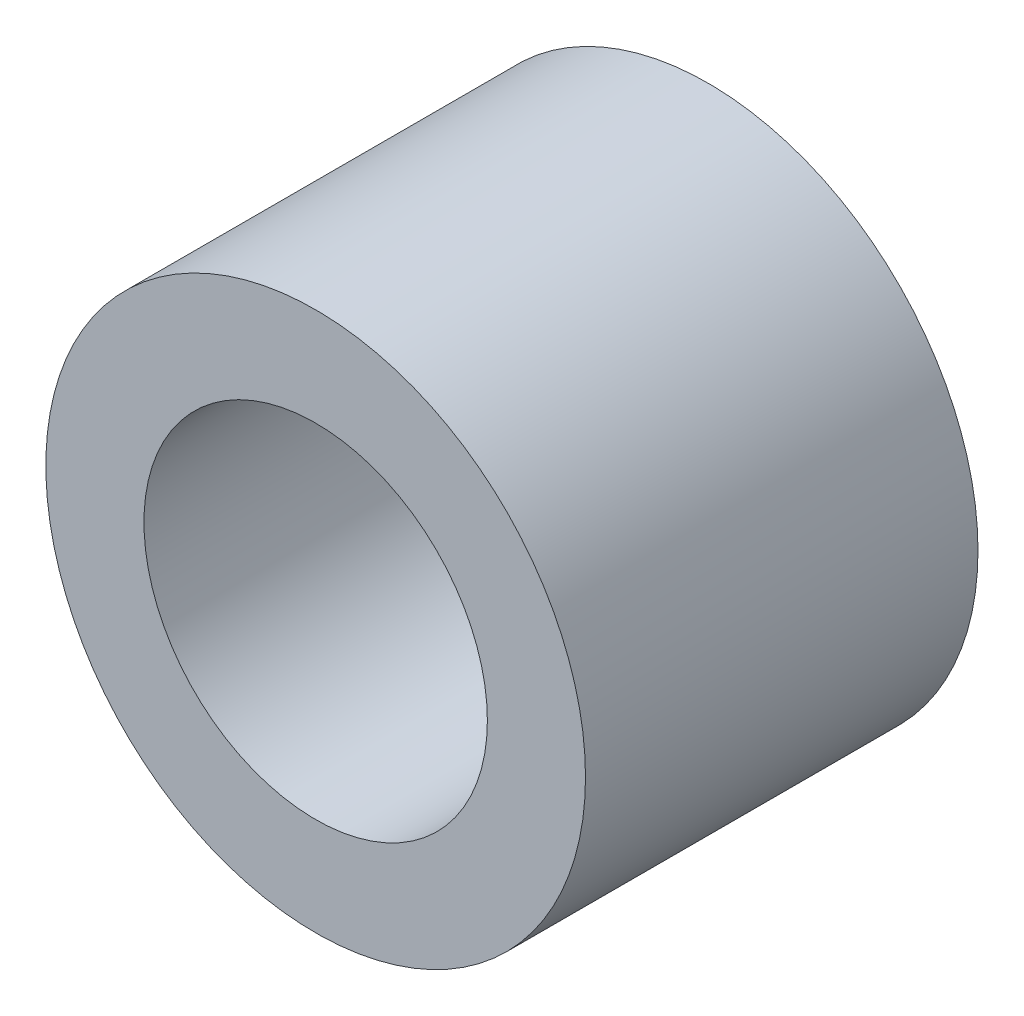
SolidWorks part; units mm, degrees
material "ABS"
ref_plane "前视基准面" through (0, 0, 0) normal (0, 0, 1) x (1, 0, 0)
ref_plane "上视基准面" through (0, 0, 0) normal (0, 1, 0) x (1, 0, 0)
ref_plane "右视基准面" through (0, 0, 0) normal (1, 0, 0) x (0, 0, -1)
sketch "草图1" plane through (0, 0, 0) normal (0, 0, 1) x (1, 0, 0)
  circle A0 centre (0, 0) radius 1.75
  circle A1 centre (0, 0) radius 2.75
  dimension "D1" = 3.5
  dimension "D2" = 5.5
extrude "凸台-拉伸1" add sketch "草图1" along normal blind 4
